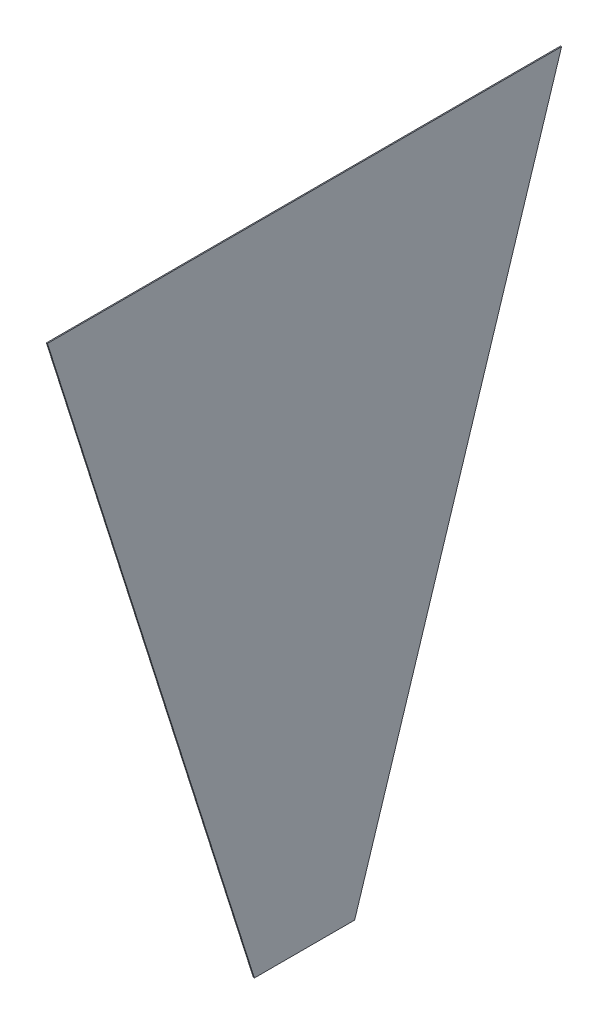
SolidWorks part; units mm, degrees
ref_plane "Front Plane" through (0, 0, 0) normal (0, 0, 1) x (1, 0, 0)
ref_plane "Top Plane" through (0, 0, 0) normal (0, 1, 0) x (1, 0, 0)
ref_plane "Right Plane" through (0, 0, 0) normal (1, 0, 0) x (0, 0, -1)
sketch "Sketch1" plane through (0, 0, 0) normal (1, 0, 0) x (0, 0, -1)
  line L0 (0, 0) -> (300, 0) construction
  line L1 (0, 0) -> (-300, 0) construction
  line L2 (-300, 0) -> (-300, 381) construction
  line L3 (300, 0) -> (300, 381) construction
  line L4 (-300, 381) -> (300, 381)
  line L5 (0, 0) -> (0, -381) construction
  line L6 (0, -381) -> (-58.5, -381)
  line L7 (0, -381) -> (58.5, -381)
  line L8 (300, 381) -> (58.5, -381)
  line L9 (-300, 381) -> (-58.5, -381)
  dimension "D1" = 300
  dimension "D2" = 381
  dimension "D3" = 381
  dimension "D4" = 58.5
  dimension "D5" = 799.3536
extrude "Boss-Extrude1" add sketch "Sketch1" along normal blind 1.22
